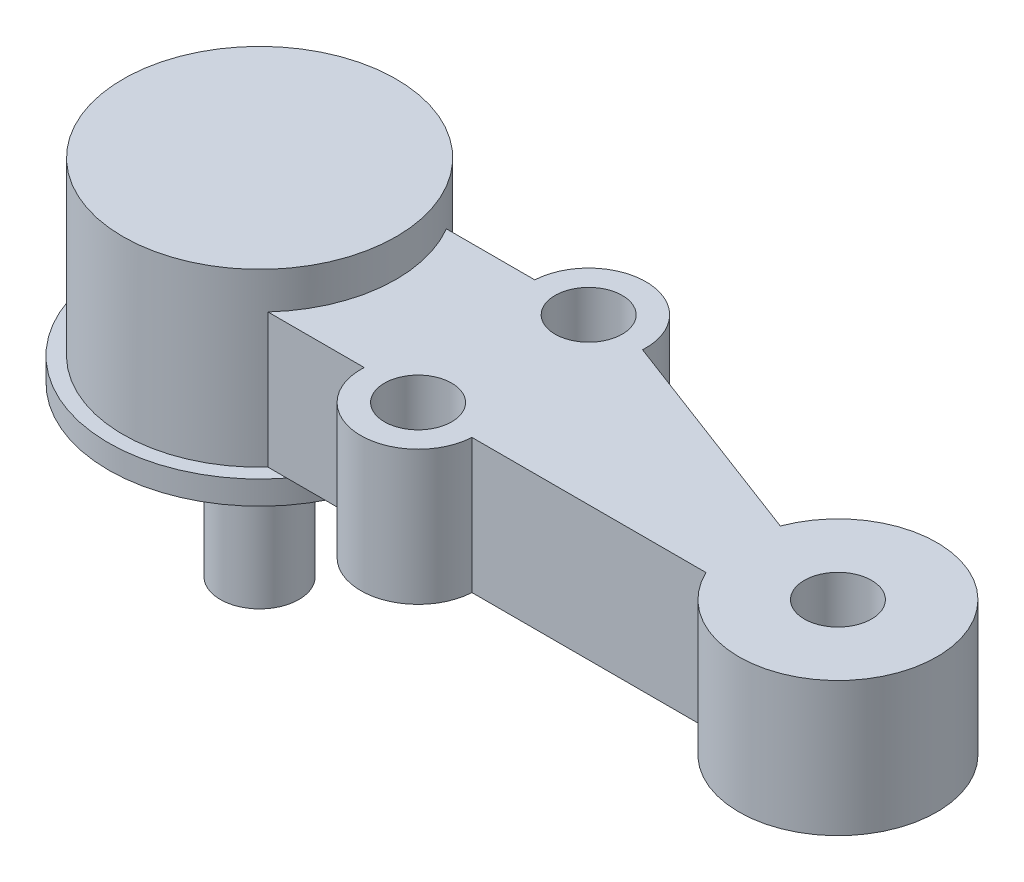
SolidWorks part; units mm, degrees
ref_plane "Front Plane" through (0, 0, 0) normal (0, 0, 1) x (1, 0, 0)
ref_plane "Top Plane" through (0, 0, 0) normal (0, 1, 0) x (1, 0, 0)
ref_plane "Right Plane" through (0, 0, 0) normal (1, 0, 0) x (0, 0, -1)
sketch "Sketch1" plane through (0, 0, 0) normal (0, 1, 0) x (1, 0, 0)
  line L0 (0.6635, 12.0281) -> (-0.7298, -11.9637) construction
  line L1 (9.1773, 11.5337) -> (42.1437, -0.9285)
  line L2 (7.784, -12.4581) -> (42.6141, -12.4581)
  line L3 (-7.8502, 12.5225) -> (-20.9955, 12.5225)
  line L4 (-9.2435, -11.4693) -> (-23.5651, -11.4693)
  arc A0 (42.6141, -12.4581) -> (42.1437, -0.9285) centre (55.931, -6.1404) ccw
  arc A1 (9.1773, 11.5337) -> (-7.8502, 12.5225) centre (0.6635, 12.0281) ccw
  arc A2 (-9.2435, -11.4693) -> (7.784, -12.4581) centre (-0.7298, -11.9637) ccw
  arc A3 (-20.9955, 12.5225) -> (-23.5651, -11.4693) centre (-38.5468, 2.2688) ccw
  circle A4 centre (0.6635, 12.0281) radius 5
  circle A5 centre (-0.7298, -11.9637) radius 5
  point P4 (-0.0331, 0.0322)
extrude "Boss-Extrude1" add sketch "Sketch1" along normal blind 20
sketch "Sketch2" plane through (0, 20, 0) normal (0, 1, 0) x (1, 0, 0)
  circle A0 centre (55.931, -6.1404) radius 5
  dimension "D1" = 10
extrude "Cut-Extrude1" cut sketch "Sketch2" against normal blind 75
sketch "Sketch3" plane through (0, 0, 0) normal (0, -1, 0) x (1, 0, 0)
  circle A0 centre (-38.5468, -2.2688) radius 22.4854
extrude "Boss-Extrude2" add sketch "Sketch3" along normal blind 3.5
sketch "Sketch4" plane through (0, 20, 0) normal (0, 1, 0) x (1, 0, 0)
  circle A1 centre (-38.5468, 2.2688) radius 20.327
extrude "Boss-Extrude3" add sketch "Sketch4" along normal blind 5.5
sketch "Sketch5" plane through (0, -3.5, 0) normal (0, -1, 0) x (1, 0, 0)
  circle A0 centre (-38.5468, -2.2688) radius 5.8535
  circle A1 centre (-38.5468, -2.2688) radius 18.0431
extrude "Cut-Extrude2" cut sketch "Sketch5" against normal blind 2
sketch "Sketch7" plane through (0, -3.5, 0) normal (0, -1, 0) x (1, 0, 0)
  circle A0 centre (-38.5468, -2.2688) radius 5.8535
extrude "Boss-Extrude5" add sketch "Sketch7" along normal blind 25
